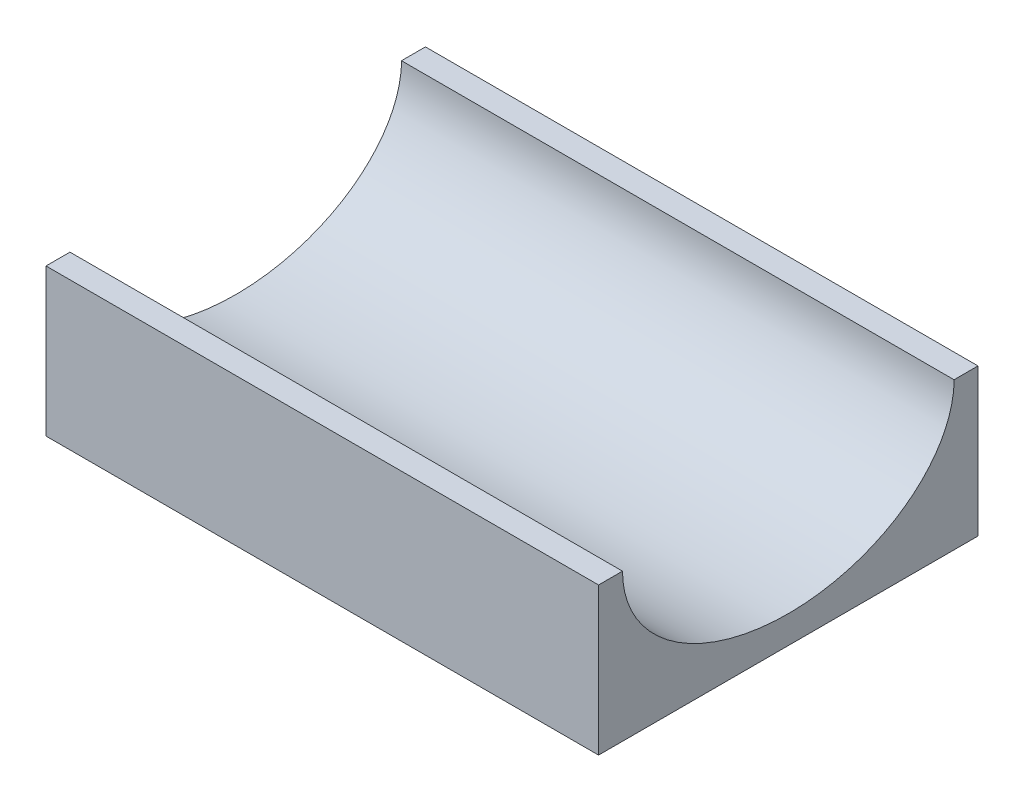
SolidWorks part; units mm, degrees
ref_plane "Front Plane" through (0, 0, 0) normal (0, 0, 1) x (1, 0, 0)
ref_plane "Top Plane" through (0, 0, 0) normal (0, 1, 0) x (1, 0, 0)
ref_plane "Right Plane" through (0, 0, 0) normal (1, 0, 0) x (0, 0, -1)
sketch "Sketch1" plane through (0, 0, 0) normal (0, 1, 0) x (1, 0, 0)
  line L1 (95.25, 0) -> (0, 0)
  line L2 (95.25, 0) -> (95.25, 65.405)
  line L3 (95.25, 65.405) -> (0, 65.405)
  line L4 (0, 0) -> (0, 65.405)
  point P0 (0, 0)
  dimension "D3" = 95.25
  dimension "D2" = 65.405
extrude "Boss-Extrude1" add sketch "Sketch1" against normal blind 4.7625
sketch "Sketch3" plane through (0, -4.7625, 0) normal (0, 1, 0) x (-1, 0, 0)
  line L0 (0, -65.405) -> (0, 0) construction
  line L1 (0, -65.405) -> (0, 0)
  line L2 (-95.25, 0) -> (-95.25, -65.405) construction
  line L3 (-95.25, -65.405) -> (0, -65.405) construction
  line L4 (0, 0) -> (-95.25, 0) construction
  line L5 (-95.25, 0) -> (-95.25, -65.405)
  line L6 (-95.25, -65.405) -> (0, -65.405)
  line L7 (0, 0) -> (-95.25, 0)
  line L8 (-3.175, -62.23) -> (-3.175, -3.175)
  line L9 (-3.175, -3.175) -> (-92.075, -3.175)
  line L10 (-92.075, -3.175) -> (-92.075, -62.23)
  line L11 (-92.075, -62.23) -> (-3.175, -62.23)
  line L12 (-5.715, -59.69) -> (-5.715, -5.715)
  line L13 (-5.715, -5.715) -> (-89.535, -5.715)
  line L14 (-89.535, -5.715) -> (-89.535, -59.69)
  line L15 (-89.535, -59.69) -> (-5.715, -59.69)
  dimension "D1" = 3.175
  dimension "D2" = 2.54
extrude "Boss-Extrude2" [suppressed] add sketch "Sketch3" against normal blind 2.54 contours L11 L10 L9 L8 L14 L15 L12 L13
sketch "Sketch4" plane through (0, 0, 0) normal (1, 0, 0) x (0, 0, -1)
  line L0 (0, 0) -> (65.405, 0)
  line L1 (4.1275, 20.6375) -> (61.2775, 20.6375) construction
  line L2 (32.7025, 20.6375) -> (32.7025, 0) construction
  line L3 (32.7025, 41.275) -> (32.7025, 0) construction
  line L4 (0, 0) -> (0, 20.6375)
  line L5 (0, 20.6375) -> (65.405, 20.6375)
  line L6 (65.405, 20.6375) -> (65.405, 0)
  ellipse E0 centre (32.7025, 20.6375) end of major axis (4.1275, 20.6375) minor radius 20.6375
  point P15 (65.405, 15.8211)
  point P17 (32.7025, 21.6827)
  point P18 (0, 0)
  dimension "D1" = 57.15
  dimension "D2" = 41.275
extrude "Boss-Extrude3" add sketch "Sketch4" along normal up to surface (95.25 mm away) contours E0 L5 L4 L0 | E0 L0 L6 L5 up to face at (95.25, -2.3813, -32.7025)
